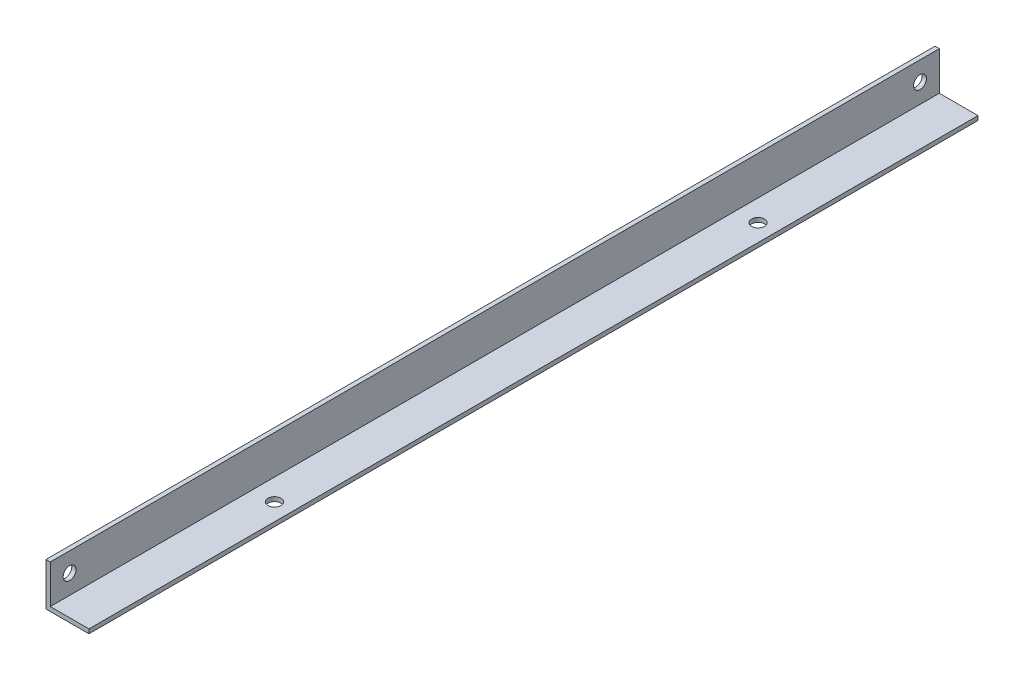
SolidWorks part; units mm, degrees
material "3.0205 (EN-AW 1200)"
ref_plane "Plan de face" through (0, 0, 0) normal (0, 0, 1) x (1, 0, 0)
ref_plane "Plan de dessus" through (0, 0, 0) normal (0, 1, 0) x (1, 0, 0)
ref_plane "Plan de droite" through (0, 0, 0) normal (1, 0, 0) x (0, 0, -1)
sketch "Esquisse1" plane through (0, 0, 0) normal (0, 0, 1) x (1, 0, 0)
  line L0 (0, 10) -> (0, 0)
  line L1 (0, 0) -> (10, 0)
  dimension "D1" = 10
  dimension "D2" = 10
extrude "Extru.-Mince1" add sketch "Esquisse1" along normal mid plane 207 thin thin type one direction reverse wall 1
sketch "Esquisse2" plane through (0, 1, 0) normal (0, 1, 0) x (1, 0, 0)
  line L0 (-5.5, 0) -> (5.5, 0) construction
  line L1 (1, -103.5) -> (1, 103.5) construction
  line L2 (10, -103.5) -> (10, 103.5) construction
  circle A0 centre (6, 56.3) radius 1.5
  circle A1 centre (6, -56.3) radius 1.5
  dimension "D1" = 112.6
  dimension "D2" = 3
  dimension "D3" = 5
  dimension "D4" = 4
extrude "Enlèv. mat.-Extru.1" cut sketch "Esquisse2" against normal blind 3
sketch "Esquisse3" plane through (1, 0, 0) normal (1, 0, 0) x (0, 0, -1)
  line L0 (0, 5.5) -> (0, -5.5) construction
  line L1 (-103.5, 1) -> (103.5, 1) construction
  line L2 (-103.5, 10) -> (-103.5, 1) construction
  line L3 (-103.5, 10) -> (103.5, 10) construction
  circle A0 centre (-99, 5.5) radius 1.5
  circle A1 centre (99, 5.5) radius 1.5
  dimension "D1" = 3
  dimension "D2" = 4.5
  dimension "D3" = 4.5
  dimension "D4" = 4.5
extrude "Enlèv. mat.-Extru.2" cut sketch "Esquisse3" against normal blind 3
